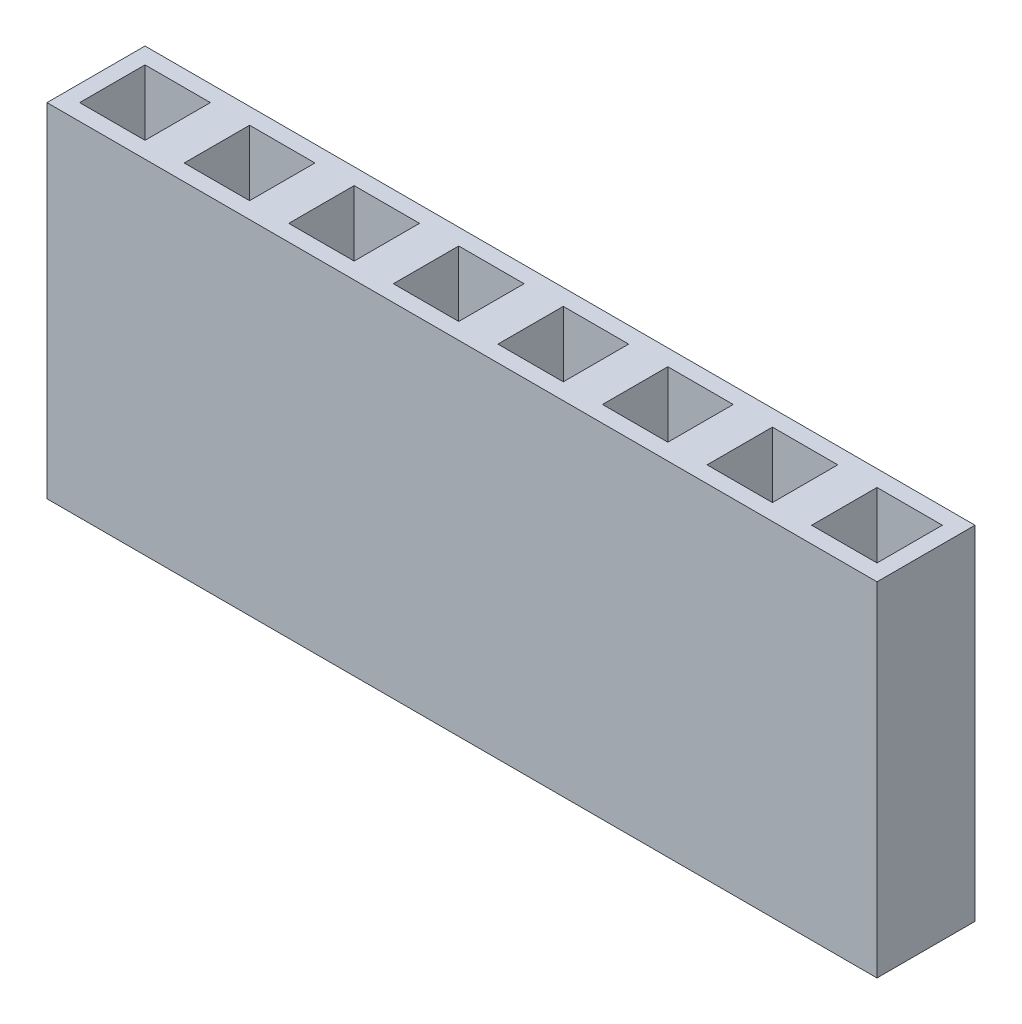
SolidWorks part; units mm, degrees
ref_plane "Plano frontal" through (0, 0, 0) normal (0, 0, 1) x (1, 0, 0)
ref_plane "Plano superior" through (0, 0, 0) normal (0, 1, 0) x (1, 0, 0)
ref_plane "Plano direito" through (0, 0, 0) normal (1, 0, 0) x (0, 0, -1)
sketch "Esboço1" plane through (0, 0, 0) normal (0, 0, 1) x (1, 0, 0)
  line L1 (-19.2, 4.2) -> (19.2, 4.2)
  line L2 (-19.2, 4.2) -> (-19.2, -4.2)
  line L3 (-19.2, -4.2) -> (19.2, -4.2)
  line L4 (19.2, 4.2) -> (19.2, -4.2)
  line L5 (-19.2, 4.2) -> (19.2, -4.2) construction
  line L6 (-19.2, -4.2) -> (19.2, 4.2) construction
  point P0 (0, 0)
  dimension "D1" = 38.4
  dimension "D2" = 8.4
extrude "Ressalto-extrusão1" add sketch "Esboço1" along normal blind 2.4
sketch "Esboço2" plane through (0, 4.2, 0) normal (0, 1, 0) x (1, 0, 0)
  line L0 (19.2, 0) -> (-19.2, 0) construction
  line L1 (-18.8, -0.4) -> (-17.2, -0.4)
  line L2 (-18.8, -0.4) -> (-18.8, -2)
  line L3 (-18.8, -2) -> (-17.2, -2)
  line L4 (-17.2, -0.4) -> (-17.2, -2)
  line L5 (-19.2, -2.4) -> (-19.2, 0) construction
  dimension "D1" = 1.6
  dimension "D2" = 1.6
  dimension "D3" = 0.4
  dimension "D4" = 0.4
extrude "Corte-extrusão1" cut sketch "Esboço2" against normal blind 2.5
pattern_linear "Padrão linear1" count 16 spacing 2.56 along (1, 0, 0) of "Corte-extrusão1"
sketch "Esboço3" plane through (0, 1.7, 0) normal (0, 1, 0) x (1, 0, 0)
  line L0 (-18.8, -0.4) -> (-17.2, -2) construction
  line L1 (-17.2, -0.4) -> (-18.8, -2) construction
  line L4 (-18.8, -0.4) -> (-18.8, -2)
  line L5 (-18.8, -2) -> (-17.2, -2)
  line L6 (-17.2, -2) -> (-17.2, -0.4)
  line L7 (-17.2, -0.4) -> (-18.8, -0.4)
  line L8 (-18.8, -0.4) -> (-18.8, -2)
  line L9 (-18.8, -2) -> (-17.2, -2)
  line L10 (-17.2, -2) -> (-17.2, -0.4)
  line L11 (-17.2, -0.4) -> (-18.8, -0.4)
  circle A0 centre (-18, -1.2) radius 0.51
  dimension "D2" = 1.02
  dimension "D1" = 0
extrude "Corte-extrusão2" cut sketch "Esboço3" against normal through all contours A0
pattern_linear "Padrão linear2" count 15 spacing 2.543 along (1, 0, 0) of "Corte-extrusão2"
ref_plane "Plano1" through (-18.8, 4.2, 2) normal (0, 0, 1) x (1, 0, 0)
sketch "Esboço6" plane through (0, 0, 2.4) normal (0, 0, 1) x (1, 0, 0)
  line L0 (1.1198, 4.2) -> (1.1198, -4.2)
  line L1 (19.2, 4.2) -> (-19.2, 4.2) construction
  line L2 (-19.2, -4.2) -> (19.2, -4.2) construction
  line L3 (1.1198, -4.2) -> (19.2, -4.2)
  line L4 (19.2, -4.2) -> (19.2, 4.2)
  line L5 (19.2, 4.2) -> (1.1198, 4.2)
extrude "Corte-extrusão3" cut sketch "Esboço6" against normal blind 10
